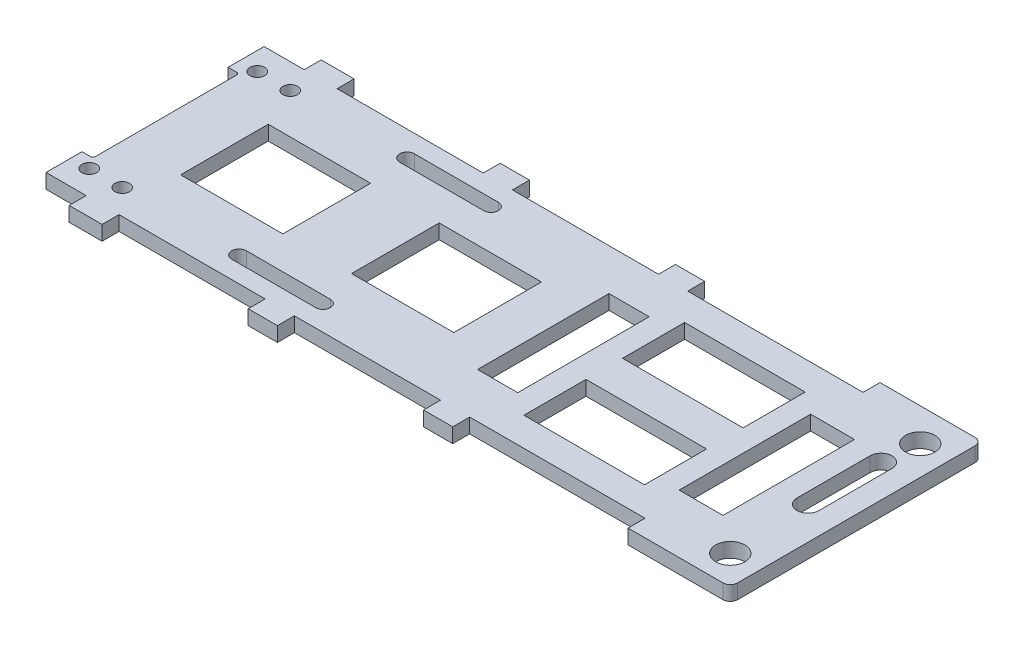
SolidWorks part; units mm, degrees
ref_plane "Front Plane" through (0, 0, 0) normal (0, 0, 1) x (1, 0, 0)
ref_plane "Top Plane" through (0, 0, 0) normal (0, 1, 0) x (1, 0, 0)
ref_plane "Right Plane" through (0, 0, 0) normal (1, 0, 0) x (0, 0, -1)
sketch "Top Plate" plane through (0, 0, 0) normal (0, 1, 0) x (1, 0, 0)
  line L0 (43.5, 7.8863) -> (43.5, -2.1137) construction
  line L1 (-48, 17.25) -> (47, 17.25)
  line L2 (-48, 17.25) -> (-48, -17.25)
  line L3 (-48, -17.25) -> (47, -17.25)
  line L4 (48, 16.25) -> (48, -16.25)
  line L5 (-48, 17.25) -> (48, -17.25) construction
  line L6 (-48, -17.25) -> (48, 17.25) construction
  line L7 (45, 7.8863) -> (45, -2.1137)
  line L8 (42, 7.8863) -> (42, -2.1137)
  line L9 (-110.9994, 0) -> (95.9069, 0) construction
  line L10 (33, 8.75) -> (39, 8.75)
  line L11 (33, 8.75) -> (33, -9.25)
  line L12 (33, -9.25) -> (39, -9.25)
  line L13 (39, 8.75) -> (39, -9.25)
  line L14 (33, 8.75) -> (39, -9.25) construction
  line L15 (33, -9.25) -> (39, 8.75) construction
  line L16 (30, -2.5) -> (13.5, -2.5)
  line L17 (30, 11) -> (13.5, 11)
  line L18 (30, 11) -> (30, 2.5)
  line L19 (30, 2.5) -> (13.5, 2.5)
  line L20 (13.5, 11) -> (13.5, 2.5)
  line L21 (30, 11) -> (13.5, 2.5) construction
  line L22 (30, 2.5) -> (13.5, 11) construction
  line L23 (13.5, -11) -> (13.5, -2.5)
  line L24 (30, -11) -> (13.5, -11)
  line L25 (30, -11) -> (30, -2.5)
  line L26 (-13.5, 11.5) -> (-25, 11.5) construction
  line L27 (10.4, 9.25) -> (4.9, 9.25)
  line L28 (10.4, 9.25) -> (10.4, -8.75)
  line L29 (10.4, -8.75) -> (4.9017, -8.75)
  line L30 (4.9, 9.25) -> (4.9017, -8.75)
  line L31 (10.4, 9.25) -> (4.9017, -8.75) construction
  line L32 (10.4, -8.75) -> (4.9, 9.25) construction
  line L33 (-1.0983, 6) -> (-15.0983, 6)
  line L34 (-1.0983, 6) -> (-1.0983, -6)
  line L35 (-1.0983, -6) -> (-15.0983, -6)
  line L36 (-15.0983, 6) -> (-15.0983, -6)
  line L37 (-1.0983, 6) -> (-15.0983, -6) construction
  line L38 (-1.0983, -6) -> (-15.0983, 6) construction
  line L39 (-24.5, 6) -> (-38.5, 6)
  line L40 (-24.5, 6) -> (-24.5, -6)
  line L41 (-24.5, -6) -> (-38.5, -6)
  line L42 (-38.5, 6) -> (-38.5, -6)
  line L43 (-24.5, 6) -> (-38.5, -6) construction
  line L44 (-24.5, -6) -> (-38.5, 6) construction
  line L45 (-13.5, 10.5) -> (-25, 10.5)
  line L46 (-13.5, 12.5) -> (-25, 12.5)
  line L47 (-13.5, -11.5) -> (-25, -11.5) construction
  line L48 (-13.5, -10.5) -> (-25, -10.5)
  line L49 (-13.5, -12.5) -> (-25, -12.5)
  line L50 (-42.5, 14.9266) -> (-48, 14.9266)
  line L51 (-48, -10) -> (-46.8, -10)
  line L52 (-48, -10) -> (-48, 10)
  line L53 (-48, 10) -> (-46.8, 10)
  line L54 (-46.5, -9.7) -> (-46.5, 9.7)
  line L55 (34, -17.25) -> (10, -17.25)
  line L56 (34, -17.25) -> (34, -14.9266)
  line L57 (34, -14.9266) -> (10, -14.9266)
  line L58 (10, -17.25) -> (10, -14.9266)
  line L59 (6, -17.25) -> (-14, -17.25)
  line L60 (6, -17.25) -> (6, -14.9266)
  line L61 (6, -14.9266) -> (-14, -14.9266)
  line L62 (-14, -17.25) -> (-14, -14.9266)
  line L63 (-18, -17.25) -> (-38, -17.25)
  line L64 (-18, -17.25) -> (-18, -14.9266)
  line L65 (-18, -14.9266) -> (-38, -14.9266)
  line L66 (-38, -17.25) -> (-38, -14.9266)
  line L67 (-42.5, -17.25) -> (-48, -17.25)
  line L68 (-42.5, -17.25) -> (-42.5, -14.9266)
  line L69 (-42.5, -14.9266) -> (-48, -14.9266)
  line L70 (-48, -17.25) -> (-48, -14.9266)
  line L71 (-48, 17.25) -> (-48, 14.9266)
  line L72 (-42.5, 17.25) -> (-48, 17.25)
  line L73 (-42.5, 17.25) -> (-42.5, 14.9266)
  line L74 (-18, 14.9266) -> (-38, 14.9266)
  line L75 (-38, 17.25) -> (-38, 14.9266)
  line L76 (-18, 17.25) -> (-38, 17.25)
  line L77 (-18, 17.25) -> (-18, 14.9266)
  line L78 (6, 14.9266) -> (-14, 14.9266)
  line L79 (-14, 17.25) -> (-14, 14.9266)
  line L80 (6, 17.25) -> (-14, 17.25)
  line L81 (6, 17.25) -> (6, 14.9266)
  line L82 (34, 14.9266) -> (10, 14.9266)
  line L83 (10, 17.25) -> (10, 14.9266)
  line L84 (34, 17.25) -> (10, 17.25)
  line L85 (34, 17.25) -> (34, 14.9266)
  circle A0 centre (44, 12.75) radius 2
  circle A1 centre (44, -13.25) radius 2
  arc A2 (45, 7.8863) -> (42, 7.8863) centre (43.5, 7.8863) ccw
  arc A3 (42, -2.1137) -> (45, -2.1137) centre (43.5, -2.1137) ccw
  arc A4 (-13.5, 10.5) -> (-13.5, 12.5) centre (-13.5, 11.5) ccw
  arc A5 (-25, 12.5) -> (-25, 10.5) centre (-25, 11.5) ccw
  arc A6 (-13.5, -10.5) -> (-13.5, -12.5) centre (-13.5, -11.5) cw
  arc A7 (-25, -12.5) -> (-25, -10.5) centre (-25, -11.5) cw
  circle A8 centre (-45.5, 11.5) radius 1
  circle A9 centre (-41, 11.5) radius 1
  circle A10 centre (-45.5, -11.5) radius 1
  circle A11 centre (-41, -11.5) radius 1
  arc A12 (48, -16.25) -> (47, -17.25) centre (47, -16.25) cw
  arc A13 (48, 16.25) -> (47, 17.25) centre (47, 16.25) ccw
  arc A14 (-46.8, -10) -> (-46.5, -9.7) centre (-46.8, -9.7) ccw
  arc A15 (-46.5, 9.7) -> (-46.8, 10) centre (-46.8, 9.7) ccw
  point P0 (0, 0)
  point P12 (43.5, 2.8863)
  point P17 (36, -0.25)
  point P24 (21.75, 6.75)
  point P33 (5.0473, 0)
  point P38 (-31.5, 0)
  point P39 (-8.0983, 0)
  point P50 (-19.25, 11.5)
  point P57 (-19.25, -11.5)
  point P80 (-47.4, 10)
  point P83 (-46.5, -10)
  point P86 (-46.5, 10)
  dimension "D3" = 4
  dimension "D4" = 4
  dimension "D5" = 4.5
  dimension "D6" = 26
  dimension "D8" = 10
  dimension "D11" = 4
  dimension "D32" = 11.5
  dimension "D35" = 2
  dimension "D37" = 2
  dimension "D38" = 4.5
  dimension "D39" = 1
  dimension "D40" = 1
  dimension "D44" = 0.3
  dimension "D45" = 0.3
  dimension "D1" = 96
  dimension "D2" = 34.5
  dimension "D7" = 4
  dimension "D9" = 3
  dimension "D10" = 3
  dimension "D12" = 6
  dimension "D13" = 18
  dimension "D14" = 3
  dimension "D15" = 8
  dimension "D16" = 8.5
  dimension "D17" = 2.5
  dimension "D18" = 16.5
  dimension "D19" = 3
  dimension "D20" = 18
  dimension "D21" = 5.5
  dimension "D22" = 3.1
  dimension "D23" = 12
  dimension "D24" = 14
  dimension "D25" = 6
  dimension "D26" = 3.1
  dimension "D27" = 12
  dimension "D28" = 14
  dimension "D29" = 9.5
  dimension "D30" = 9.4017
  dimension "D31" = 2
  dimension "D33" = 10.5
  dimension "D34" = 23
  dimension "D36" = 2.5
  dimension "D41" = 1.5
  dimension "D42" = 20
  dimension "D43" = 10
  dimension "D46" = 14
  dimension "D47" = 24
  dimension "D48" = 4
  dimension "D49" = 20
  dimension "D50" = 4
  dimension "D51" = 20
  dimension "D52" = 4.5
extrude "Top Plate Extrude" add sketch "Top Plate" along normal blind 2 contours A15 L54 A14 L51 L2 L69 L68 L3 L66 L65 L64 L62 L61 L60 L58 L57 L56 A12 L4 A13 L1 L85 L82 L83 L81 L78 L79 L77 L74 L75 L73 L50 L53 A11 L49 A7 L48 A6 L10 L13 L12
